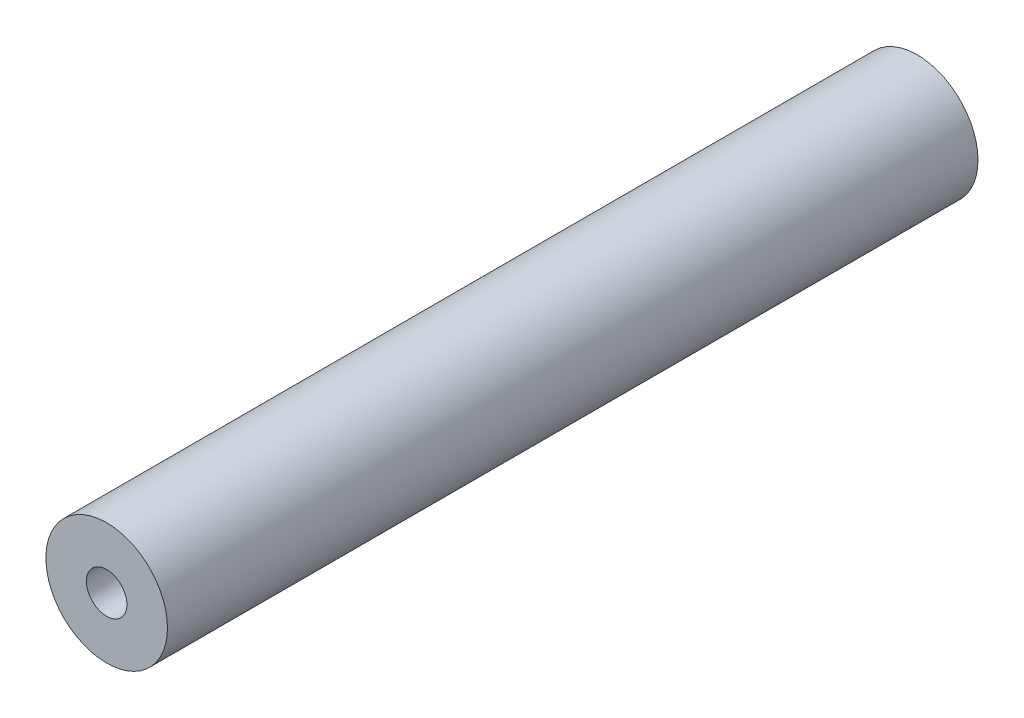
SolidWorks part; units mm, degrees
ref_plane "Front Plane" through (0, 0, 0) normal (0, 0, 1) x (1, 0, 0)
ref_plane "Top Plane" through (0, 0, 0) normal (0, 1, 0) x (1, 0, 0)
ref_plane "Right Plane" through (0, 0, 0) normal (1, 0, 0) x (0, 0, -1)
sketch "Sketch1" plane through (0, 0, 0) normal (0, 0, 1) x (1, 0, 0)
  circle A0 centre (0, 0) radius 4.7625
  circle A1 centre (0, 0) radius 1.5875
  dimension "D1" = 9.525
  dimension "D2" = 3.175
extrude "Boss-Extrude1" add sketch "Sketch1" along normal blind 63.5 contours A1 | A0
